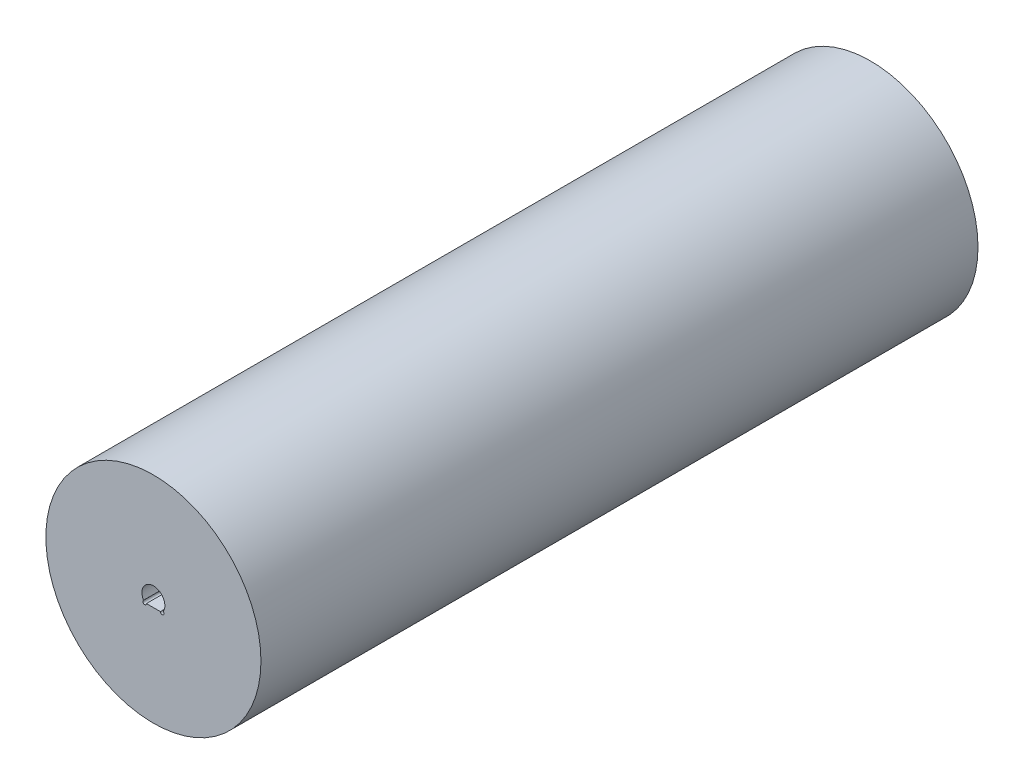
SolidWorks part; units mm, degrees
ref_plane "Front Plane" through (0, 0, 0) normal (0, 0, 1) x (1, 0, 0)
ref_plane "Top Plane" through (0, 0, 0) normal (0, 1, 0) x (1, 0, 0)
ref_plane "Right Plane" through (0, 0, 0) normal (1, 0, 0) x (0, 0, -1)
sketch "Sketch1" plane through (0, 0, 0) normal (0, 0, 1) x (1, 0, 0)
  circle A0 centre (0, 0) radius 15
  dimension "D1" = 30
extrude "Boss-Extrude1" add sketch "Sketch1" along normal blind 100
sketch "Sketch2" plane through (0, 0, 100) normal (0, 0, 1) x (1, 0, 0)
  line L0 (-0.975, -1.0293) -> (0.975, -1.0293)
  arc A0 (1.3704, -0.8259) -> (-1.3704, -0.8259) centre (0, 0) ccw
  arc A1 (-1.3704, -0.8259) -> (-0.975, -1.0293) centre (-1.225, -1.0293) ccw
  arc A2 (0.975, -1.0293) -> (1.3704, -0.8259) centre (1.225, -1.0293) ccw
  dimension "D1" = 3.2
  dimension "D3" = 0.5
  dimension "D4" = 0.5
  dimension "D2" = 2.45
extrude "Cut-Extrude1" cut sketch "Sketch2" against normal blind 10
sketch "Sketch3" plane through (0, 0, 0) normal (0, 0, -1) x (-1, 0, 0)
  circle A0 centre (0, 0) radius 11
  dimension "D1" = 22
extrude "Cut-Extrude2" cut sketch "Sketch3" against normal blind 7
sketch "Sketch4" plane through (0, 0, 7) normal (0, 0, -1) x (-1, 0, 0)
  circle A0 centre (0, 0) radius 5
  dimension "D1" = 10
extrude "Cut-Extrude3" cut sketch "Sketch4" against normal blind 70
